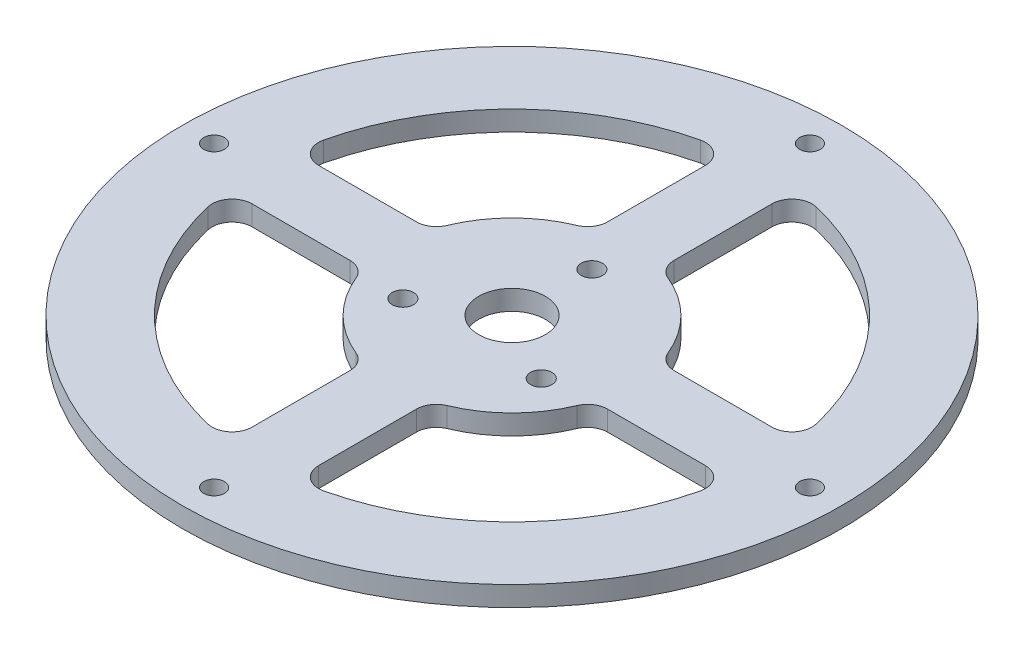
SolidWorks part; units mm, degrees
ref_plane "前视基准面" through (0, 0, 0) normal (0, 0, 1) x (1, 0, 0)
ref_plane "上视基准面" through (0, 0, 0) normal (0, 1, 0) x (1, 0, 0)
ref_plane "右视基准面" through (0, 0, 0) normal (1, 0, 0) x (0, 0, -1)
sketch "草图1" plane through (0, 0, 0) normal (0, 1, 0) x (1, 0, 0)
  line L0 (-115.8758, 0) -> (200.9305, 0) construction
  line L1 (0, 84.1656) -> (0, -95.7235) construction
  line L2 (0, 0) -> (128.8522, -74.3928) construction
  line L3 (0, 0) -> (-106.0602, -61.2339) construction
  line L4 (-34.0459, 5) -> (-19.3553, 5)
  line L5 (-5, 34.0459) -> (-5, 19.3553)
  line L6 (34.0459, 5) -> (19.3553, 5)
  line L7 (5, 34.0459) -> (5, 19.3553)
  line L8 (34.0459, -5) -> (19.3553, -5)
  line L9 (5, -34.0459) -> (5, -19.3553)
  line L10 (-34.0459, -5) -> (-19.3553, -5)
  line L11 (-5, -34.0459) -> (-5, -19.3553)
  circle A0 centre (0, 0) radius 49.5
  circle A1 centre (0, 44.75) radius 1.55
  circle A2 centre (-44.75, 0) radius 1.55
  circle A3 centre (0, -44.75) radius 1.55
  circle A4 centre (44.75, 0) radius 1.55
  circle A5 centre (0, 0) radius 5
  circle A6 centre (0, 0) radius 12 construction
  circle A7 centre (0, 12) radius 1.6
  circle A8 centre (10.3923, -6) radius 1.6
  circle A9 centre (-10.3923, -6) radius 1.6
  circle A10 centre (0, 0) radius 17.9434 construction
  circle A11 centre (0, 0) radius 37.9732 construction
  arc A12 (-8.6862, 36.9664) -> (-36.9664, 8.6862) centre (0, 0) ccw
  arc A13 (-6.8541, 16.5828) -> (-16.5828, 6.8541) centre (0, 0) ccw
  arc A14 (6.8541, 16.5828) -> (16.5828, 6.8541) centre (0, 0) cw
  arc A15 (8.6862, 36.9664) -> (36.9664, 8.6862) centre (0, 0) cw
  arc A16 (6.8541, -16.5828) -> (16.5828, -6.8541) centre (0, 0) ccw
  arc A17 (8.6862, -36.9664) -> (36.9664, -8.6862) centre (0, 0) ccw
  arc A18 (-6.8541, -16.5828) -> (-16.5828, -6.8541) centre (0, 0) cw
  arc A19 (-8.6862, -36.9664) -> (-36.9664, -8.6862) centre (0, 0) cw
  arc A20 (-34.0459, 5) -> (-36.9664, 8.6862) centre (-34.0459, 8) cw
  arc A21 (-16.5828, 6.8541) -> (-19.3553, 5) centre (-19.3553, 8) cw
  arc A22 (-6.8541, 16.5828) -> (-5, 19.3553) centre (-8, 19.3553) ccw
  arc A23 (-5, 34.0459) -> (-8.6862, 36.9664) centre (-8, 34.0459) ccw
  arc A24 (8.6862, 36.9664) -> (5, 34.0459) centre (8, 34.0459) ccw
  arc A25 (34.0459, 5) -> (36.9664, 8.6862) centre (34.0459, 8) ccw
  arc A26 (19.3553, 5) -> (16.5828, 6.8541) centre (19.3553, 8) cw
  arc A27 (5, 19.3553) -> (6.8541, 16.5828) centre (8, 19.3553) ccw
  arc A28 (36.9664, -8.6862) -> (34.0459, -5) centre (34.0459, -8) ccw
  arc A29 (19.3553, -5) -> (16.5828, -6.8541) centre (19.3553, -8) ccw
  arc A30 (5, -19.3553) -> (6.8541, -16.5828) centre (8, -19.3553) cw
  arc A31 (8.6862, -36.9664) -> (5, -34.0459) centre (8, -34.0459) cw
  arc A32 (-5, -34.0459) -> (-8.6862, -36.9664) centre (-8, -34.0459) cw
  arc A33 (-6.8541, -16.5828) -> (-5, -19.3553) centre (-8, -19.3553) cw
  arc A34 (-19.3553, -5) -> (-16.5828, -6.8541) centre (-19.3553, -8) cw
  arc A35 (-34.0459, -5) -> (-36.9664, -8.6862) centre (-34.0459, -8) ccw
  point P49 (-37.6426, 5)
  point P52 (-17.2327, 5)
  point P55 (-5, 17.2327)
  point P58 (-5, 37.6426)
  point P61 (5, 37.6426)
  point P64 (37.6426, 5)
  point P67 (17.2327, 5)
  point P70 (5, 17.2327)
  point P73 (37.6426, -5)
  point P76 (17.2327, -5)
  point P79 (5, -17.2327)
  point P82 (5, -37.6426)
  point P85 (-5, -37.6426)
  point P88 (-5, -17.2327)
  point P91 (-17.2327, -5)
  point P94 (-37.6426, -5)
  dimension "D1" = 89.5
  dimension "D3" = 99
  dimension "D4" = 240
  dimension "D6" = 10
  dimension "D8" = 3
  dimension "D9" = 3
  dimension "D10" = 3
  dimension "D11" = 3
  dimension "D12" = 3
  dimension "D13" = 3
  dimension "D14" = 3
  dimension "D15" = 3.1
  dimension "D16" = 3.1
  dimension "D17" = 3.1
  dimension "D18" = 3.1
  dimension "D2" = 89.5
  dimension "D5" = 120
  dimension "D7" = 10
extrude "凸台-拉伸1" add sketch "草图1" along normal blind 3
